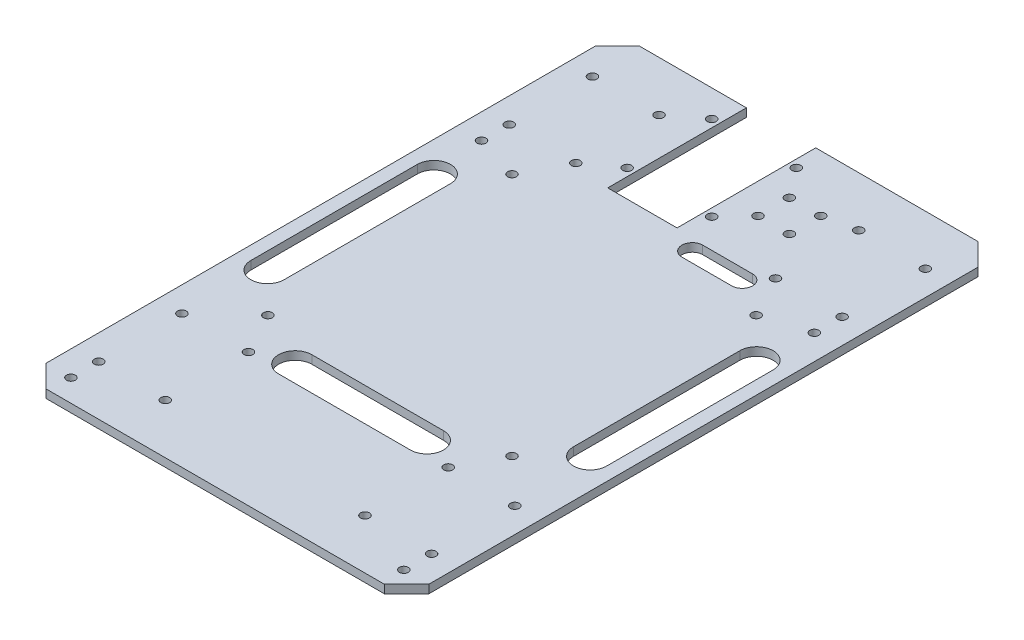
SolidWorks part; units mm, degrees
ref_plane "前视基准面" through (0, 0, 0) normal (0, 0, 1) x (1, 0, 0)
ref_plane "上视基准面" through (0, 0, 0) normal (0, 1, 0) x (1, 0, 0)
ref_plane "右视基准面" through (0, 0, 0) normal (1, 0, 0) x (0, 0, -1)
sketch "草图1" plane through (0, 0, 0) normal (0, 1, 0) x (1, 0, 0)
  line L0 (0, 144.9284) -> (0, -144.9284) construction
  line L1 (-61, 107) -> (-22.5, 107)
  line L2 (-69, 99) -> (-69, -99)
  line L3 (-61, -107) -> (61, -107)
  line L4 (69, 99) -> (69, -99)
  line L5 (-69, 107) -> (69, -107) construction
  line L6 (-69, -107) -> (69, 107) construction
  line L7 (-61, 107) -> (-69, 99)
  line L8 (61, 107) -> (69, 99)
  line L9 (-69, -99) -> (-61, -107)
  line L10 (69, -99) -> (61, -107)
  line L11 (-97.1437, 37) -> (97.1437, 37) construction
  line L12 (-128.7779, 0) -> (128.7779, 0) construction
  line L14 (-47.5, 47.5) -> (47.5, 47.5) construction
  line L15 (-47.5, 47.5) -> (-47.5, -47.5) construction
  line L16 (-47.5, -47.5) -> (47.5, -47.5) construction
  line L17 (47.5, 47.5) -> (47.5, -47.5) construction
  line L18 (-47.5, 47.5) -> (47.5, -47.5) construction
  line L19 (-47.5, -47.5) -> (47.5, 47.5) construction
  line L22 (-22.5, 107) -> (-22.5, 57)
  line L23 (-22.5, 57) -> (2.5, 57)
  line L24 (2.5, 107) -> (2.5, 57)
  line L25 (19, 81) -> (33.0934, 81) construction
  line L27 (19, 81) -> (19, 70.6487) construction
  line L28 (19, 81) -> (24.6569, 75.3431) construction
  line L29 (-10, 57) -> (-10, 107) construction
  line L30 (0, 30) -> (-83.2466, 30) construction
  line L31 (0, -30) -> (-83.2466, -30) construction
  line L32 (-58.1585, 30) -> (-58.1585, -30) construction
  line L33 (-52.1585, 30) -> (-52.1585, -30)
  line L34 (-64.1585, 30) -> (-64.1585, -30)
  line L35 (58.1585, 30) -> (58.1585, -30) construction
  line L36 (52.1585, 30) -> (52.1585, -30)
  line L37 (64.1585, 30) -> (64.1585, -30)
  line L38 (-23.75, -47.5) -> (-23.75, -115.8847) construction
  line L39 (23.75, -47.5) -> (23.75, -115.8847) construction
  line L40 (-23.75, -54.4034) -> (23.75, -54.4034) construction
  line L41 (-23.75, -48.4034) -> (23.75, -48.4034)
  line L42 (-23.75, -60.4034) -> (23.75, -60.4034)
  line L43 (-23.75, 47.5) -> (-23.75, 65.8701) construction
  line L44 (23.75, 47.5) -> (23.75, 65.8701) construction
  line L45 (12.5, 52.5128) -> (30.4587, 52.5128) construction
  line L46 (12.5, 56.2628) -> (30.4587, 56.2628)
  line L47 (12.5, 48.7628) -> (30.4587, 48.7628)
  line L49 (2.5, 107) -> (61, 107)
  circle A0 centre (60, 59) radius 1.6
  circle A1 centre (36, 59) radius 1.6
  circle A2 centre (60, 89) radius 1.6
  circle A3 centre (36, 89) radius 1.6
  circle A4 centre (-60, 89) radius 1.6
  circle A5 centre (-60, 59) radius 1.6
  circle A6 centre (-36, 89) radius 1.6
  circle A7 centre (-36, 59) radius 1.6
  circle A8 centre (60, -59) radius 1.6
  circle A9 centre (60, -89) radius 1.6
  circle A10 centre (36, -59) radius 1.6
  circle A11 centre (36, -89) radius 1.6
  circle A12 centre (-36, -59) radius 1.6
  circle A13 centre (-36, -89) radius 1.6
  circle A14 centre (-60, -59) radius 1.6
  circle A15 centre (-60, -89) radius 1.6
  circle A16 centre (44, 44) radius 1.6
  circle A23 centre (60, 49) radius 1.6
  circle A24 centre (60, -99) radius 1.6
  circle A25 centre (-44, 44) radius 1.6
  circle A26 centre (44, -44) radius 1.6
  circle A27 centre (-44, -44) radius 1.6
  circle A28 centre (-60, -99) radius 1.6
  circle A29 centre (-60, 49) radius 1.6
  arc A38 (-52.1585, 30) -> (-64.1585, 30) centre (-58.1585, 30) ccw
  circle A39 centre (19, 81) radius 8 construction
  circle A40 centre (24.6569, 75.3431) radius 1.6
  circle A44 centre (-25.25, 97.25) radius 1.6
  circle A45 centre (5.25, 97.25) radius 1.6
  circle A46 centre (-25.25, 66.75) radius 1.6
  circle A47 centre (5.25, 66.75) radius 1.6
  arc A48 (-64.1585, -30) -> (-52.1585, -30) centre (-58.1585, -30) ccw
  arc A49 (52.1585, 30) -> (64.1585, 30) centre (58.1585, 30) cw
  arc A50 (64.1585, -30) -> (52.1585, -30) centre (58.1585, -30) cw
  arc A51 (-23.75, -48.4034) -> (-23.75, -60.4034) centre (-23.75, -54.4034) ccw
  arc A52 (23.75, -60.4034) -> (23.75, -48.4034) centre (23.75, -54.4034) ccw
  arc A53 (12.5, 56.2628) -> (12.5, 48.7628) centre (12.5, 52.5128) ccw
  arc A54 (30.4587, 48.7628) -> (30.4587, 56.2628) centre (30.4587, 52.5128) ccw
  circle A55 centre (13.3431, 75.3431) radius 1.6
  circle A56 centre (13.3431, 86.6569) radius 1.6
  circle A57 centre (24.6569, 86.6569) radius 1.6
  point P0 (0, 0)
  point P9 (0, 0)
  point P20 (0, 37)
  point P39 (0, 0)
  point P63 (0, 0)
  point P76 (0, -81.5)
  point P98 (20.9033, 77.0928)
  point P112 (-58.1585, 0)
  point P119 (58.1585, 0)
  point P130 (0, -54.4034)
  point P141 (21.4794, 52.5128)
  point P147 (19, 81)
  dimension "D10" = 3.2
  dimension "D17" = 3.2
  dimension "D22" = 3.2
  dimension "D24" = 3.2
  dimension "D30" = 16
  dimension "D31" = 3.2
  dimension "D34" = 3.2
  dimension "D39" = 23.75
  dimension "D1" = 138
  dimension "D2" = 214
  dimension "D3" = 70
  dimension "D4" = 22
  dimension "D5" = 9
  dimension "D12" = 24
  dimension "D14" = 30
  dimension "D16" = 9
  dimension "D18" = 44
  dimension "D19" = 44
  dimension "D20" = 95
  dimension "D21" = 95
  dimension "D23" = 10
  dimension "D25" = 10
  dimension "D26" = 148
  dimension "D27" = 120
  dimension "D28" = 50
  dimension "D29" = 25
  dimension "D33" = 4
  dimension "D32" = 45
  dimension "D35" = 9.75
  dimension "D36" = 15.25
  dimension "D38" = 30
  dimension "D40" = 23.75
  dimension "D41" = 26
  dimension "D42" = 12
  dimension "D43" = 12
  dimension "D44" = 7.5
  dimension "D45" = 26
  dimension "D46" = 29
  dimension "D11" = 2
  dimension "D13" = 2
  dimension "D15" = 2
  dimension "D37" = 2
extrude "凸台-拉伸2" add sketch "草图1" along normal blind 3
